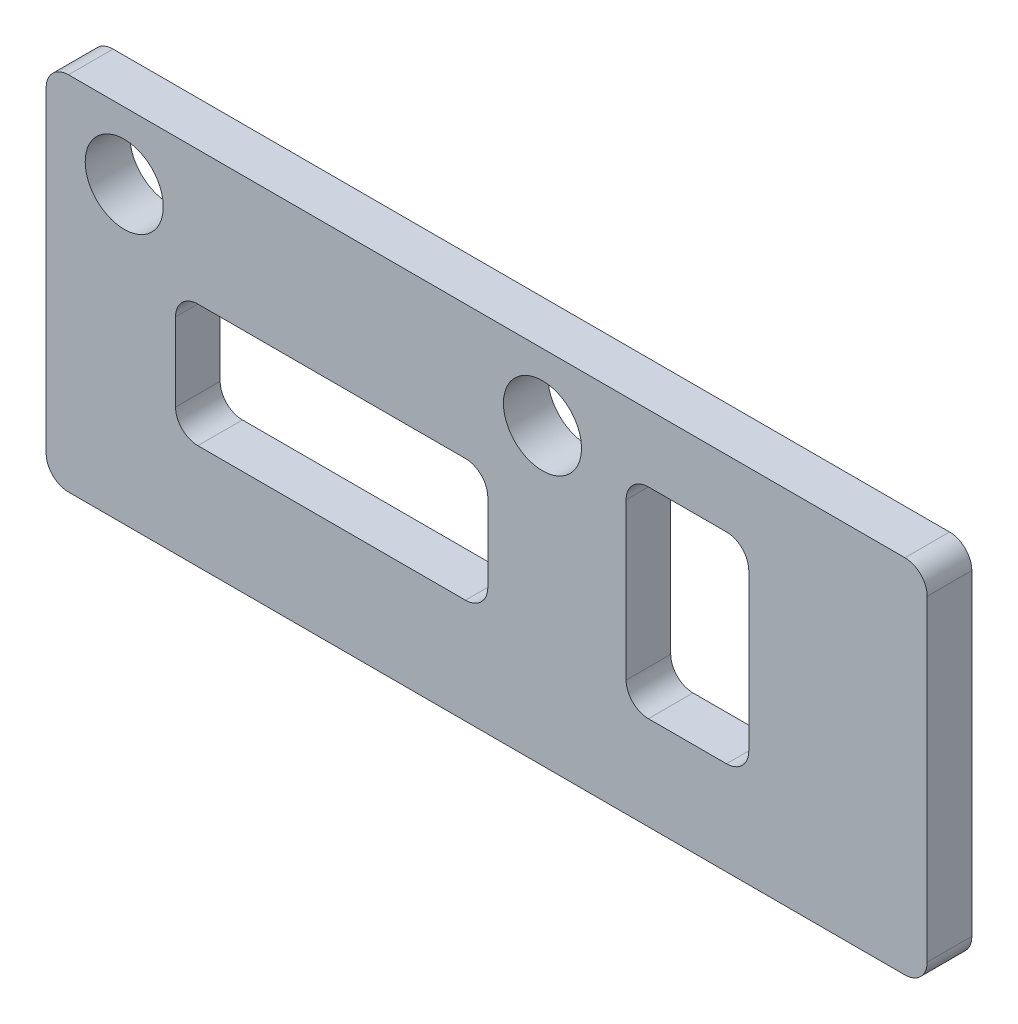
SolidWorks part; units mm, degrees
ref_plane "Front" through (0, 0, 0) normal (0, 0, 1) x (1, 0, 0)
ref_plane "Top" through (0, 0, 0) normal (0, 1, 0) x (1, 0, 0)
ref_plane "Right" through (0, 0, 0) normal (1, 0, 0) x (0, 0, -1)
sketch "Sketch1" plane through (0, 0, 0) normal (0, 0, 1) x (1, 0, 0)
  line L0 (7.25, 5.1) -> (10.75, 5.1)
  line L1 (11.75, 4.1) -> (11.75, -2.9)
  line L2 (10.75, -3.9) -> (7.25, -3.9)
  line L3 (6.25, -2.9) -> (6.25, 4.1)
  line L4 (-12.95, 2.1) -> (-0.95, 2.1)
  line L5 (0.05, 1.1) -> (0.05, -2.4)
  line L6 (-0.95, -3.4) -> (-12.95, -3.4)
  line L7 (-13.95, -2.4) -> (-13.95, 1.1)
  line L8 (-19.75, 7.1) -> (-19.75, -7.1)
  line L9 (-18.75, -8.1) -> (18.75, -8.1)
  line L10 (19.75, -7.1) -> (19.75, 7.1)
  line L11 (18.75, 8.1) -> (-18.75, 8.1)
  arc A0 (10.75, 5.1) -> (11.75, 4.1) centre (10.75, 4.1) cw
  arc A1 (11.75, -2.9) -> (10.75, -3.9) centre (10.75, -2.9) cw
  arc A2 (7.25, -3.9) -> (6.25, -2.9) centre (7.25, -2.9) cw
  arc A3 (6.25, 4.1) -> (7.25, 5.1) centre (7.25, 4.1) cw
  arc A4 (-0.95, 2.1) -> (0.05, 1.1) centre (-0.95, 1.1) cw
  arc A5 (0.05, -2.4) -> (-0.95, -3.4) centre (-0.95, -2.4) cw
  arc A6 (-12.95, -3.4) -> (-13.95, -2.4) centre (-12.95, -2.4) cw
  arc A7 (-13.95, 1.1) -> (-12.95, 2.1) centre (-12.95, 1.1) cw
  circle A8 centre (-16.25, 5.1) radius 1.75
  circle A9 centre (2.5, 5.1) radius 1.75
  arc A10 (-18.75, 8.1) -> (-19.75, 7.1) centre (-18.75, 7.1) ccw
  arc A11 (-19.75, -7.1) -> (-18.75, -8.1) centre (-18.75, -7.1) ccw
  arc A12 (18.75, -8.1) -> (19.75, -7.1) centre (18.75, -7.1) ccw
  arc A13 (19.75, 7.1) -> (18.75, 8.1) centre (18.75, 7.1) ccw
  point P40 (0, -8.1)
  point P42 (19.75, 0)
  dimension "D5" = 3.5
  dimension "D9" = 1
  dimension "D1" = 16.2
  dimension "D2" = 39.5
  dimension "D3" = 9
  dimension "D4" = 5.5
  dimension "D6" = 18.75
  dimension "D7" = 5.5
  dimension "D8" = 14
  dimension "D10" = 4.2
  dimension "D11" = 8
  dimension "D12" = 3
  dimension "D13" = 3.5
  dimension "D14" = 4.7
  dimension "D15" = 5.8
extrude "Boss-Extrude1" add sketch "Sketch1" against normal blind 2
